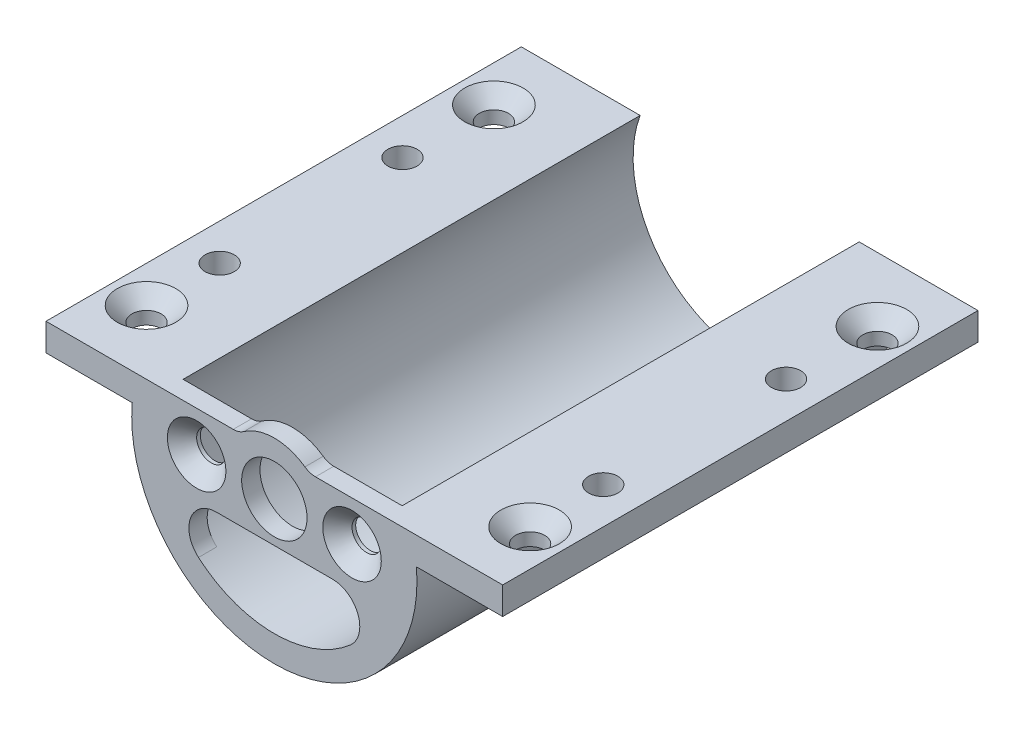
SolidWorks part; units mm, degrees
ref_plane "Front Plane" through (0, 0, 0) normal (0, 0, 1) x (1, 0, 0)
ref_plane "Top Plane" through (0, 0, 0) normal (0, 1, 0) x (1, 0, 0)
ref_plane "Right Plane" through (0, 0, 0) normal (1, 0, 0) x (0, 0, -1)
sketch "Sketch1" plane through (0, 0, 0) normal (0, 0, 1) x (1, 0, 0)
  line L0 (27.4167, 0) -> (-27.4253, 0) construction
  line L1 (-11.9811, 4.3608) -> (-14.9811, 4.3608)
  line L2 (11.9811, 4.3608) -> (14.9811, 4.3608)
  line L3 (-14.9811, 4.3608) -> (-24.9811, 4.3608)
  line L4 (-24.9811, 4.3608) -> (-24.9811, 1.3608)
  line L5 (-24.9811, 1.3608) -> (-15.5434, 1.3608)
  line L6 (0, 0) -> (0, 15.0202) construction
  line L7 (14.9811, 4.3608) -> (24.9811, 4.3608)
  line L8 (24.9811, 4.3608) -> (24.9811, 1.3608)
  line L9 (24.9811, 1.3608) -> (15.5434, 1.3608)
  arc A0 (11.9811, 4.3608) -> (-11.9811, 4.3608) centre (0, 0) cw
  arc A1 (14.9811, 4.3608) -> (-14.9811, 4.3608) centre (0, 0) cw
  point P0 (0, 0)
  point P7 (-12.75, 0)
  point P9 (0, 0)
  point P10 (12.75, 0)
  dimension "D1" = 12.75
  dimension "D2" = 20
  dimension "D3" = 20
  dimension "D4" = 3
  dimension "D5" = 10
  dimension "D6" = 3
  dimension "D7" = 10
  dimension "D8" = 3
extrude "Boss-Extrude1" add sketch "Sketch1" against normal blind 52 contours A1 L2 A0 L1 | L5 A1 L3 L4 | L7 A1 L9 L8
sketch "Sketch3" plane through (0, 0, 0) normal (0, 0, 1) x (1, 0, 0)
  line L0 (0, 0) -> (-8.797, 0) construction
  line L1 (-11.9811, 4.3608) -> (11.9811, 4.3608)
  line L2 (-11.9667, -4.4) -> (11.9667, -4.4)
  arc A0 (-11.9811, 4.3608) -> (11.9811, 4.3608) centre (0, 0) ccw construction
  circle A1 centre (0, 0) radius 3.575
  arc A2 (3.81, 4.3608) -> (-3.81, 4.3608) centre (0, 0) ccw
  arc M10 (11.9811, 4.3608) -> (-11.9811, 4.3608) centre (0, 0) cw
  dimension "D2" = 7.15
  dimension "D1" = 4.4
extrude "Boss-Extrude2" add sketch "Sketch3" against normal blind 2 contours L0 A1 L2 M10 | L0 L1 A1 M10 | L1 A2
fillet "Fillet2" radius 2 2 edges at (3.81, 4.3608, -1) (-3.81, 4.3608, -1)
sketch "Sketch4" plane through (0, 0, 0) normal (0, 0, 1) x (1, 0, 0)
  line L0 (-8.5, -4.4) -> (-8.5, 4.3608) construction
  line L1 (-11.9667, -4.4) -> (11.9667, -4.4) construction
  line L2 (-4.4984, 4.3608) -> (-24.9811, 4.3608) construction
  line L3 (8.5, -4.4) -> (8.5, 4.3608) construction
  point P0 (8.5, -0.0196)
  point P10 (-8.5, -0.0196)
  dimension "D1" = 8.5
  dimension "D2" = 8.5
hole_wizard "Hole1" positions "3DSketch2" profile "Sketch7" legacy end condition through all
sketch3d "3DSketch2"
  point P0 (-8.5, -0.0196, 0)
  point P3 (8.5, -0.0196, 0)
sketch "Sketch7" plane through (-8.5, -0.0196, 0) normal (1, 0, 0) x (0, -1, 0)
  line L0 (0, 0) -> (0, 51.9754)
  line L1 (0, 51.9754) -> (1.6, 51.9754)
  line L2 (1.6, 51.9754) -> (1.6, 1.6)
  line L3 (1.6, 1.6) -> (3.2, 0)
  line L4 (3.2, 0) -> (0, 0)
  line L5 (0, -6.4453) -> (0, 115.525) construction
  line L6 (-1.6, 1.6) -> (-3.2, 0) construction
  dimension "Diameter" = 3.2
  dimension "Depth" = 52
  dimension "C-Sink Angle" = 90
  dimension "C-Sink Diameter" = 6.4
sketch "Sketch8" plane through (0, 4.3608, 0) normal (0, 1, 0) x (1, 0, 0)
  line L0 (-20.9811, 52) -> (-20.9811, 0) construction
  line L1 (-11.9811, 52) -> (-24.9811, 52) construction
  line L2 (-4.4984, 0) -> (-24.9811, 0) construction
  line L3 (-24.9811, 52) -> (-24.9811, 0) construction
  line L4 (20.9811, 52) -> (20.9811, 0) construction
  line L5 (-11.9811, 52) -> (-24.9811, 52) construction
  line L6 (24.9811, 52) -> (24.9811, 0) construction
  line L7 (11.9811, 52) -> (24.9811, 52) construction
  line L8 (0, 52) -> (0, 0) construction
  line L9 (12.75, 52) -> (-12.75, 52) construction
  point P14 (-20.9811, 35)
  point P15 (-20.9811, 15)
  point P16 (20.9811, 15)
  point P17 (20.9811, 35)
  point P18 (20.9811, 45)
  point P20 (20.9811, 7)
  point P23 (0, 0)
  point P29 (-20.9811, 7)
  point P30 (-20.9811, 45)
  dimension "D1" = 4
  dimension "D2" = 4
  dimension "D3" = 15
  dimension "D4" = 15
  dimension "D5" = 17
  dimension "D6" = 17
  dimension "D7" = 38
  dimension "D8" = 7
hole_wizard "Hole2" positions "3DSketch3" profile "Sketch9" legacy end condition through all
sketch3d "3DSketch3"
  point P0 (-20.9811, 4.3608, -35)
  point P3 (-20.9811, 4.3608, -15)
  point P6 (20.9811, 4.3608, -15)
  point P9 (20.9811, 4.3608, -35)
sketch "Sketch9" plane through (-20.9811, 4.3608, -35) normal (1, 0, 0) x (0, 0, 1)
  line L0 (0, 0) -> (0, 19.9636)
  line L1 (0, 19.9636) -> (1.6, 19.9636)
  line L2 (1.6, 19.9636) -> (1.6, 0)
  line L3 (1.6, 0) -> (0, 0)
  line L4 (0, 110) -> (0, -10) construction
  dimension "Diameter" = 3.2
  dimension "Depth" = 19.9636
hole_wizard "Hole3" positions "3DSketch4" profile "Sketch10" legacy end condition through all
sketch3d "3DSketch4"
  point P0 (-20.9811, 4.3608, -7)
  point P3 (-20.9811, 4.3608, -45)
  point P6 (20.9811, 4.3608, -45)
  point P9 (20.9811, 4.3608, -7)
sketch "Sketch10" plane through (-20.9811, 4.3608, -7) normal (1, 0, 0) x (0, 0, 1)
  line L0 (0, 0) -> (0, 19.9636)
  line L1 (0, 19.9636) -> (1.6, 19.9636)
  line L2 (1.6, 19.9636) -> (1.6, 1.6)
  line L3 (1.6, 1.6) -> (3.2, 0)
  line L4 (3.2, 0) -> (0, 0)
  line L5 (0, -6.4453) -> (0, 115.525) construction
  line L6 (-1.6, 1.6) -> (-3.2, 0) construction
  dimension "Diameter" = 3.2
  dimension "Depth" = 19.9636
  dimension "C-Sink Angle" = 90
  dimension "C-Sink Diameter" = 6.4
fillet "Fillet1" radius 3 2 edges at (-11.9667, -4.4, -1) (11.9667, -4.4, -1)
